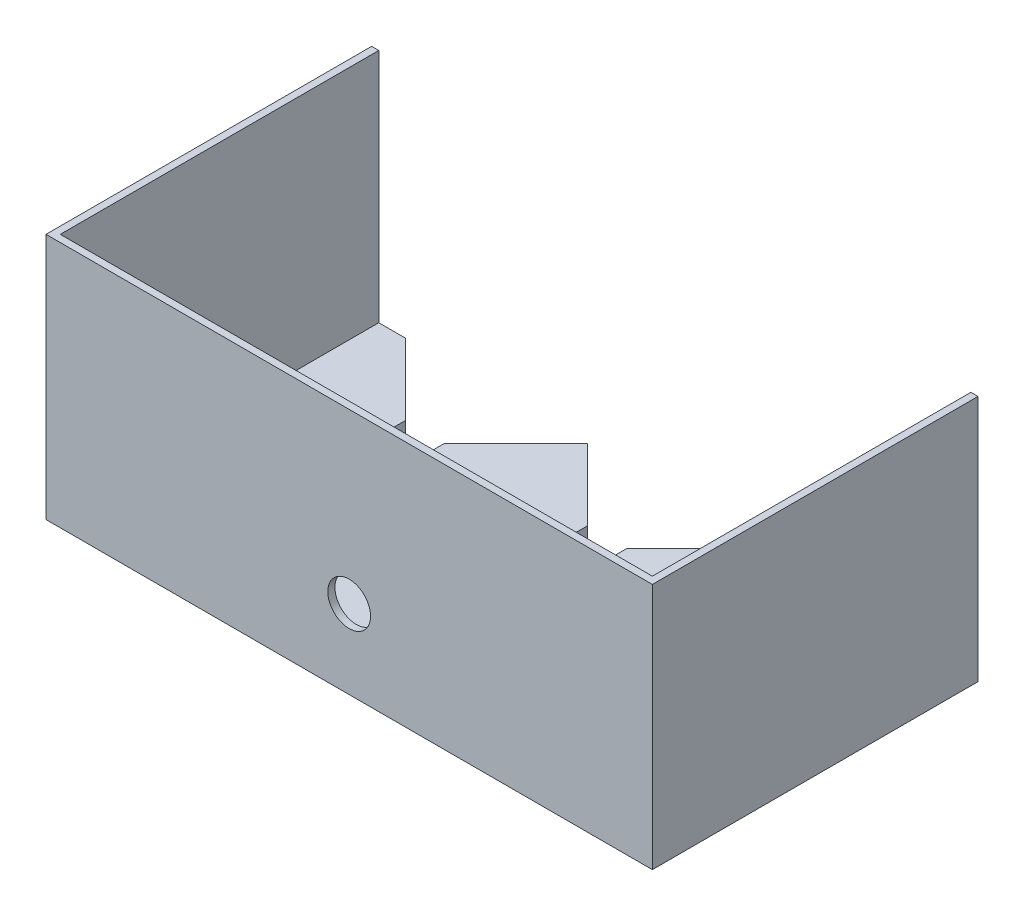
SolidWorks part; units mm, degrees
ref_plane "Front Plane" through (0, 0, 0) normal (0, 0, 1) x (1, 0, 0)
ref_plane "Top Plane" through (0, 0, 0) normal (0, 1, 0) x (1, 0, 0)
ref_plane "Right Plane" through (0, 0, 0) normal (1, 0, 0) x (0, 0, -1)
sketch "Sketch1" plane through (0, 0, 0) normal (0, 1, 0) x (1, 0, 0)
  line L0 (-69.5241, -40.7776) -> (-69.5241, 249.2224)
  line L1 (-69.5241, 249.2224) -> (-39.5241, 249.2224)
  line L2 (-39.5241, 249.2224) -> (24.1156, 185.5828)
  line L3 (24.1156, 185.5828) -> (24.1156, 105.5828)
  line L4 (24.1156, 105.5828) -> (59.1156, 105.5828)
  line L5 (59.1156, 105.5828) -> (59.1156, 185.5828)
  line L6 (59.1156, 185.5828) -> (122.7552, 249.2224)
  line L7 (122.7552, 249.2224) -> (186.3948, 185.5828)
  line L8 (186.3948, 185.5828) -> (186.3948, 105.5828)
  line L9 (186.3948, 105.5828) -> (221.3948, 105.5828)
  line L10 (221.3948, 105.5828) -> (221.3948, 185.5828)
  line L11 (221.3948, 185.5828) -> (283.2476, 247.4356)
  line L12 (283.2476, 247.4356) -> (346.8872, 183.796)
  line L13 (346.8872, 183.796) -> (346.8872, 105.5828)
  line L14 (346.8872, 105.5828) -> (381.8872, 105.5828)
  line L15 (381.8872, 105.5828) -> (381.8872, 185.5828)
  line L16 (381.8872, 185.5828) -> (445.5268, 249.2224)
  line L17 (445.5268, 249.2224) -> (470.4759, 249.2224)
  line L18 (470.4759, 249.2224) -> (470.4759, -40.7776)
  line L19 (-69.5241, -40.7776) -> (470.4759, -40.7776)
  line L21 (-69.5241, 249.2224) -> (-76.0834, 249.2224)
  line L22 (-69.5241, 249.2224) -> (-69.5241, -40.7776)
  line L23 (-69.5241, -40.7776) -> (-76.0834, -40.7776)
  line L24 (-76.0834, 249.2224) -> (-76.0834, -40.7776)
  dimension "D2" = 24.1156
  dimension "D3" = 59.1156
  dimension "D4" = 122.7552
  dimension "D5" = 283.2476
  dimension "D6" = 105.5828
  dimension "D7" = 183.796
  dimension "D8" = 40.7776
  dimension "D10" = 470.4759
  dimension "D12" = 69.5241
extrude "Boss-Extrude5" add sketch "Sketch1" along normal blind 10 contours L0 L19 L18 L17 L16 L15 L14 L13 L12 L11 L10 L9 L8 L7 L6 L5 L4 L3 L2 L1
sketch "Sketch5" plane through (0, 10, 0) normal (0, 1, 0) x (1, 0, 0)
  line L0 (-69.5241, -40.7776) -> (-69.5241, 249.2224)
  line L1 (-69.5241, 249.2224) -> (-63.1741, 249.2224)
  line L2 (-69.5241, 249.2224) -> (-39.5241, 249.2224) construction
  line L3 (-63.1741, 249.2224) -> (-63.1741, -34.4276)
  line L4 (-63.1741, -34.4276) -> (464.1259, -34.4276)
  line L5 (464.1259, -34.4276) -> (464.1259, 249.2224)
  line L6 (445.5268, 249.2224) -> (470.4759, 249.2224) construction
  line L7 (464.1259, 249.2224) -> (470.4759, 249.2224)
  line L8 (470.4759, 249.2224) -> (470.4759, -40.7776)
  line L9 (470.4759, -40.7776) -> (-69.5241, -40.7776)
  dimension "D1" = 6.35
  dimension "D2" = 283.65
  dimension "D3" = 527.3
extrude "Boss-Extrude6" add sketch "Sketch5" along normal blind 210 contours L0 L1 L3 L4 L5 L7 L8 L9
sketch "Sketch6" plane through (0, 0, 0) normal (0, 0, 1) x (1, 0, 0)
  line L0 (470.4759, 220) -> (-69.5241, 220) construction
  circle A0 centre (200.4759, 70) radius 19.05
  point P2 (175.4965, 65.0254)
  point P3 (0, 0)
  point P4 (0, 0)
  point P7 (200.4759, 220)
  dimension "D1" = 38.1
  dimension "D2" = 150
extrude "Cut-Extrude1" cut sketch "Sketch6" against normal through all both and the other way through all contours A0
